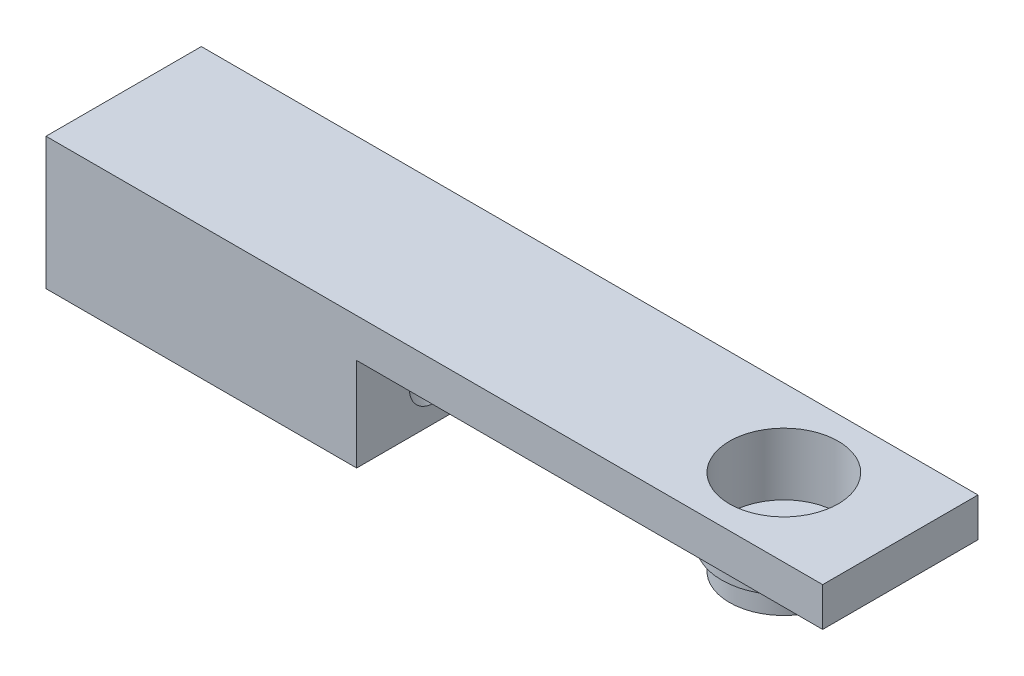
SolidWorks part; units mm, degrees
ref_plane "Спереди" through (0, 0, 0) normal (0, 0, 1) x (1, 0, 0)
ref_plane "Сверху" through (0, 0, 0) normal (0, 1, 0) x (1, 0, 0)
ref_plane "Справа" through (0, 0, 0) normal (1, 0, 0) x (0, 0, -1)
sketch "Эскиз1" plane through (0, 0, 0) normal (1, 0, 0) x (0, 0, -1)
  line L1 (-37.7241, 2.354) -> (-17.7241, 2.354)
  line L2 (-37.7241, 2.354) -> (-37.7241, 19.354)
  line L3 (-37.7241, 19.354) -> (-17.7241, 19.354)
  line L4 (-17.7241, 2.354) -> (-17.7241, 19.354)
  dimension "D1" = 17
  dimension "D2" = 20
extrude "Бобышка-Вытянуть1" add sketch "Эскиз1" along normal blind 40
sketch "Эскиз2" plane through (40, 0, 0) normal (1, 0, 0) x (0, 0, -1)
  line L0 (-27.7241, 19.354) -> (-27.7241, -9.226) construction
  line L1 (-17.7241, 19.354) -> (-37.7241, 19.354) construction
  line L3 (-17.7241, 2.354) -> (-17.7241, 19.354) construction
  line L4 (-46.9913, 14.354) -> (-2.5903, 14.354) construction
  line L6 (-37.7241, 19.354) -> (-17.7241, 19.354)
  line L7 (-37.7241, 19.354) -> (-37.7241, 14.354)
  line L8 (-37.7241, 14.354) -> (-17.7241, 14.354)
  line L9 (-17.7241, 19.354) -> (-17.7241, 14.354)
  dimension "D1" = 5
  dimension "D2" = 20
extrude "Бобышка-Вытянуть2" add sketch "Эскиз2" along normal blind 60
sketch "Эскиз3" plane through (0, 14.354, 0) normal (0, -1, 0) x (1, 0, 0)
  line L1 (100, 37.7241) -> (100, 17.7241) construction
  line L2 (85, 27.7241) -> (85, 17.7241) construction
  line L3 (100, 17.7241) -> (40, 17.7241) construction
  line L4 (85, 27.7241) -> (100, 27.7241) construction
  circle A0 centre (85, 27.7241) radius 8
  dimension "D1" = 15
  dimension "D2" = 10
extrude "Бобышка-Вытянуть3" add sketch "Эскиз3" along normal blind 3
sketch "Эскиз4" plane through (0, 11.354, 0) normal (0, -1, 0) x (1, 0, 0)
  line L0 (93, 27.7241) -> (69.3301, 27.7241) construction
  line L1 (85, 27.7241) -> (85, 37.9572) construction
  circle A0 centre (85, 27.7241) radius 8 construction
  circle A1 centre (85, 27.7241) radius 8 construction
  circle A2 centre (85, 27.7241) radius 7
extrude "Бобышка-Вытянуть4" add sketch "Эскиз4" along normal blind 3
hole_wizard "Зенковка для винта с полупотайной головкой M32" positions "Эскиз14" profile "Эскиз15" countersink size "M3" standard "ISO"
sketch "Эскиз14" plane through (40, 0, 0) normal (1, 0, 0) x (0, 0, -1)
  point P0 (-27.791, 7.7841)
sketch "Эскиз15" plane through (40, 7.7841, 27.791) normal (0, 1, 0) x (0, 0, -1)
  line L0 (0, 0) -> (0, 40)
  line L1 (0, 40) -> (1.7, 40)
  line L2 (1.7, 40) -> (1.7, 1.45)
  line L3 (1.7, 1.45) -> (3.15, 0)
  line L5 (3.15, 0) -> (0, 0)
  line L6 (-1.7, 1.45) -> (-3.15, 0) construction
  line L11 (0, -6.35) -> (0, 107.95) construction
  dimension "Диаметр сквозного отверстия" = 3.4
  dimension "Глубина сквозного отверстия" = 40
  dimension "Диаметр передней зенковки" = 6.3
  dimension "Угол передней зенковки" = 90
sketch "Эскиз16" plane through (0, 19.354, 0) normal (0, 1, 0) x (1, 0, 0)
  line L0 (100, -27.7241) -> (85, -27.7241) construction
  line L1 (100, -17.7241) -> (100, -37.7241) construction
  line L2 (85, -27.7241) -> (85, -37.7241) construction
  line L3 (100, -37.7241) -> (0, -37.7241) construction
  circle A0 centre (85, -27.7241) radius 7
  dimension "D1" = 15
  dimension "D2" = 10
extrude "Вырез-Вытянуть1" cut sketch "Эскиз16" against normal blind 8
